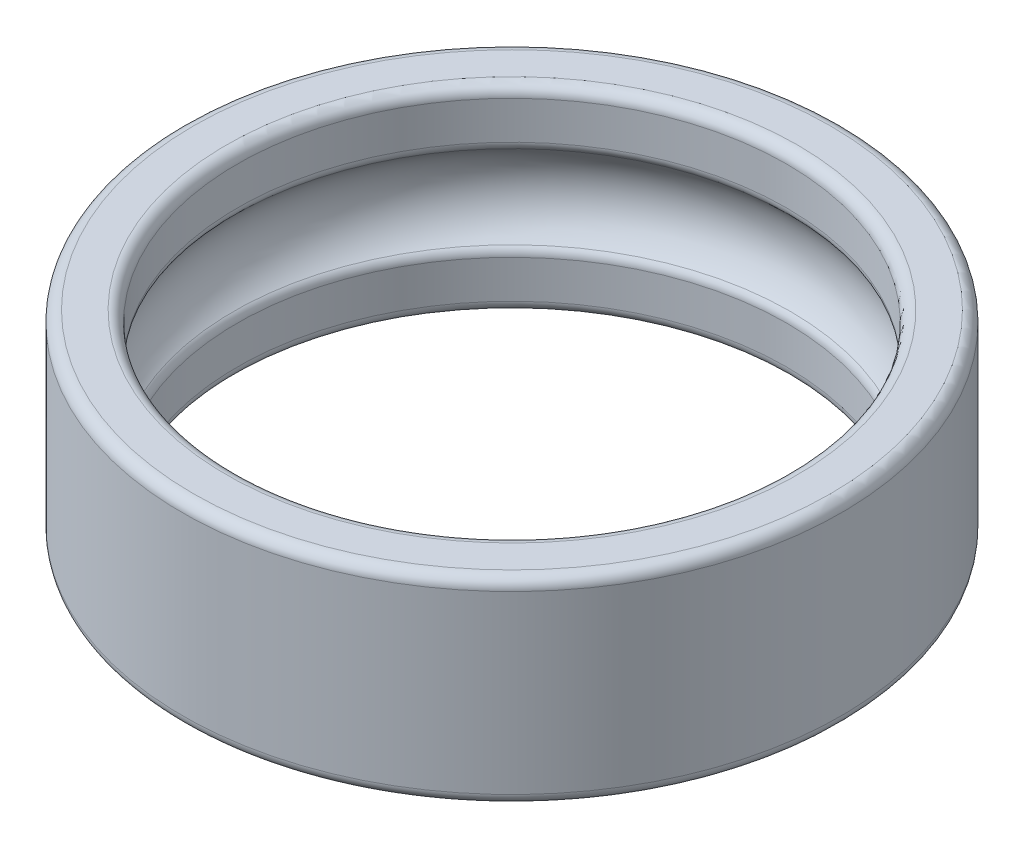
SolidWorks part; units mm, degrees
ref_plane "Front Plane" through (0, 0, 0) normal (0, 0, 1) x (1, 0, 0)
ref_plane "Top Plane" through (0, 0, 0) normal (0, 1, 0) x (1, 0, 0)
ref_plane "Right Plane" through (0, 0, 0) normal (1, 0, 0) x (0, 0, -1)
sketch "Sketch1" plane through (0, 0, 0) normal (1, 0, 0) x (0, 0, -1)
  line L0 (0, 0) -> (0, 22.6339) construction
  line L1 (25, -8) -> (25, -4.539)
  line L2 (26, 9) -> (29, 9)
  line L4 (30, 8) -> (30, -8)
  line L5 (29, -9) -> (26, -9)
  line L6 (25, 0) -> (7.4586, 0) construction
  line L7 (25, 0) -> (27.05, 0) construction
  line L8 (25, 4.539) -> (25, 8)
  arc A0 (25.3388, -3.7888) -> (25.3388, 3.7888) centre (22, 0) ccw
  arc A1 (25.3388, 3.7888) -> (25, 4.539) centre (26, 4.539) cw
  arc A2 (25.3388, -3.7888) -> (25, -4.539) centre (26, -4.539) ccw
  arc A3 (25, -8) -> (26, -9) centre (26, -8) ccw
  arc A4 (30, -8) -> (29, -9) centre (29, -8) cw
  arc A5 (29, 9) -> (30, 8) centre (29, 8) cw
  arc A6 (25, 8) -> (26, 9) centre (26, 8) cw
  point P15 (25, 4.0623)
  dimension "D4" = 10.1
  dimension "D6" = 1
  dimension "D1" = 18
  dimension "D2" = 30
  dimension "D3" = 5
  dimension "D5" = 22
revolve "Revolve1" add sketch "Sketch1" angle 360 about L0
